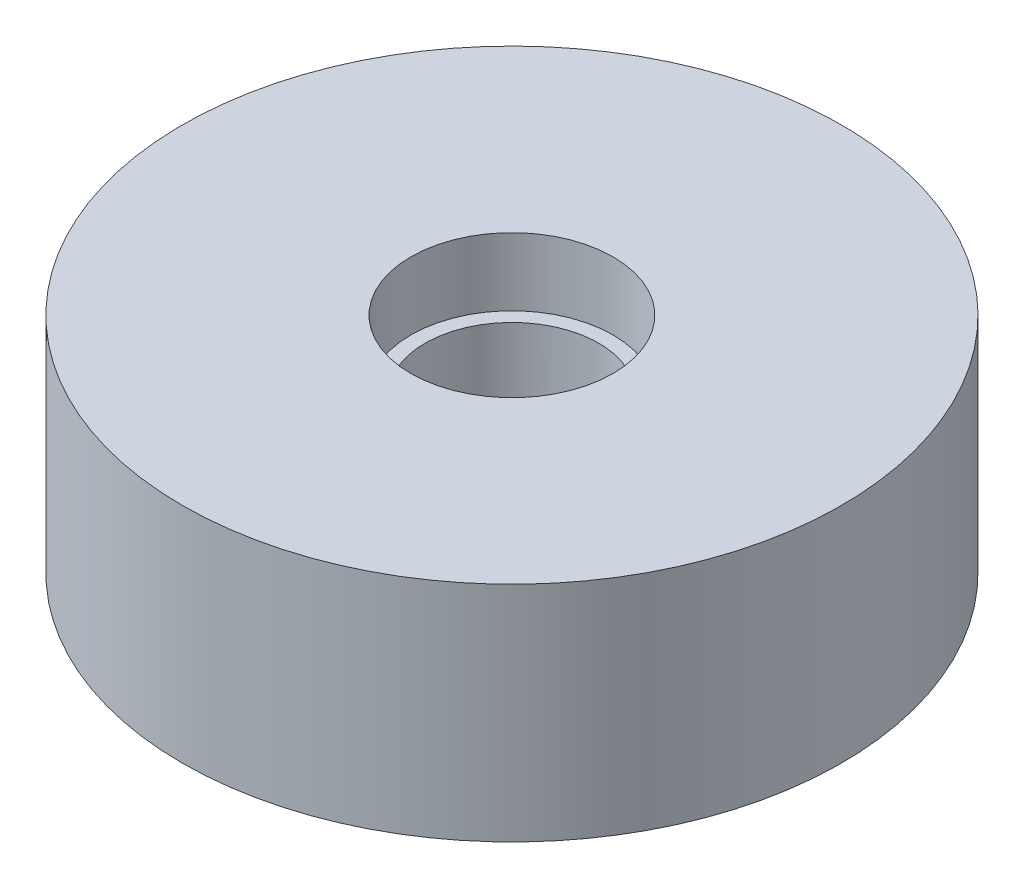
SolidWorks part; units mm, degrees
ref_plane "Front Plane" through (0, 0, 0) normal (0, 0, 1) x (1, 0, 0)
ref_plane "Top Plane" through (0, 0, 0) normal (0, 1, 0) x (1, 0, 0)
ref_plane "Right Plane" through (0, 0, 0) normal (1, 0, 0) x (0, 0, -1)
sketch "Sketch1" plane through (0, 0, 0) normal (0, 1, 0) x (1, 0, 0)
  circle A0 centre (0, 0) radius 35.814
  dimension "D1" = 71.628
extrude "Boss-Extrude1" add sketch "Sketch1" along normal blind 24.257
sketch "Sketch2" plane through (0, 24.257, 0) normal (0, 1, 0) x (1, 0, 0)
  circle A0 centre (0, 0) radius 9.4361
  dimension "D1" = 18.8722
extrude "Cut-Extrude1" cut sketch "Sketch2" against normal through all
sketch "Sketch3" plane through (0, 24.257, 0) normal (0, 1, 0) x (1, 0, 0)
  circle A0 centre (0, 0) radius 10.9855
  dimension "D1" = 21.971
extrude "Cut-Extrude2" cut sketch "Sketch3" against normal blind 7.3533
sketch "Sketch4" plane through (0, 0, 0) normal (0, -1, 0) x (1, 0, 0)
  circle A0 centre (0, 0) radius 10.9855
  dimension "D1" = 21.971
extrude "Cut-Extrude3" cut sketch "Sketch4" against normal blind 7.3533
